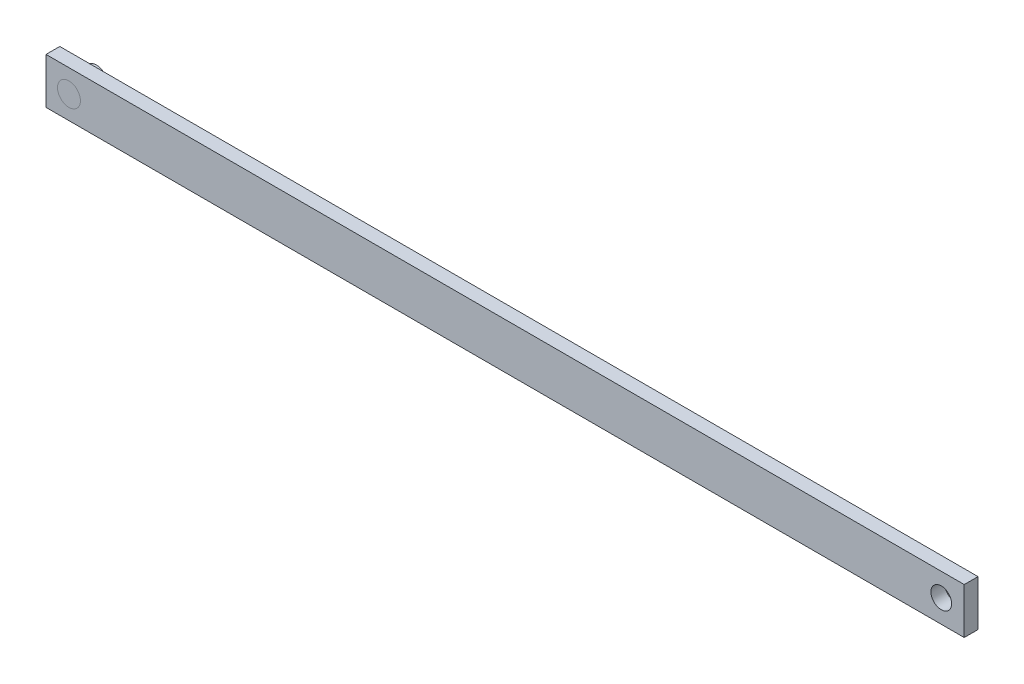
SolidWorks part; units mm, degrees
material "Sapin"
ref_plane "Plan de face" through (0, 0, 0) normal (0, 0, 1) x (1, 0, 0)
ref_plane "Plan de dessus" through (0, 0, 0) normal (0, 1, 0) x (1, 0, 0)
ref_plane "Plan de droite" through (0, 0, 0) normal (1, 0, 0) x (0, 0, -1)
sketch "Esquisse1" plane through (0, 0, 0) normal (0, 0, 1) x (1, 0, 0)
  line L1 (-200, -10) -> (200, -10)
  line L2 (-200, -10) -> (-200, 10)
  line L3 (-200, 10) -> (200, 10)
  line L4 (200, -10) -> (200, 10)
  line L5 (-200, -10) -> (200, 10) construction
  line L6 (-200, 10) -> (200, -10) construction
  point P0 (0, 0)
  dimension "D1" = 20
  dimension "D2" = 400
extrude "Boss.-Extru.1" add sketch "Esquisse1" along normal blind 6
sketch "Esquisse2" plane through (0, 0, 6) normal (0, 0, 1) x (1, 0, 0)
  line L0 (200, -10) -> (200, 10) construction
  line L1 (-200, 10) -> (-200, -10) construction
  circle A0 centre (190, 0) radius 4.5
  circle A1 centre (-190, 0) radius 5
  dimension "D1" = 9
  dimension "D3" = 10
  dimension "D4" = 10
  dimension "D2" = 10
extrude "Enlèv. mat.-Extru.1" cut sketch "Esquisse2" against normal through all
sketch "Esquisse3" plane through (0, 0, 6) normal (0, 0, 1) x (1, 0, 0)
  circle A0 centre (-190, 0) radius 5
  circle A1 centre (-190, 0) radius 5 construction
extrude "Boss.-Extru.2" add sketch "Esquisse3" against normal blind 12 separate body
